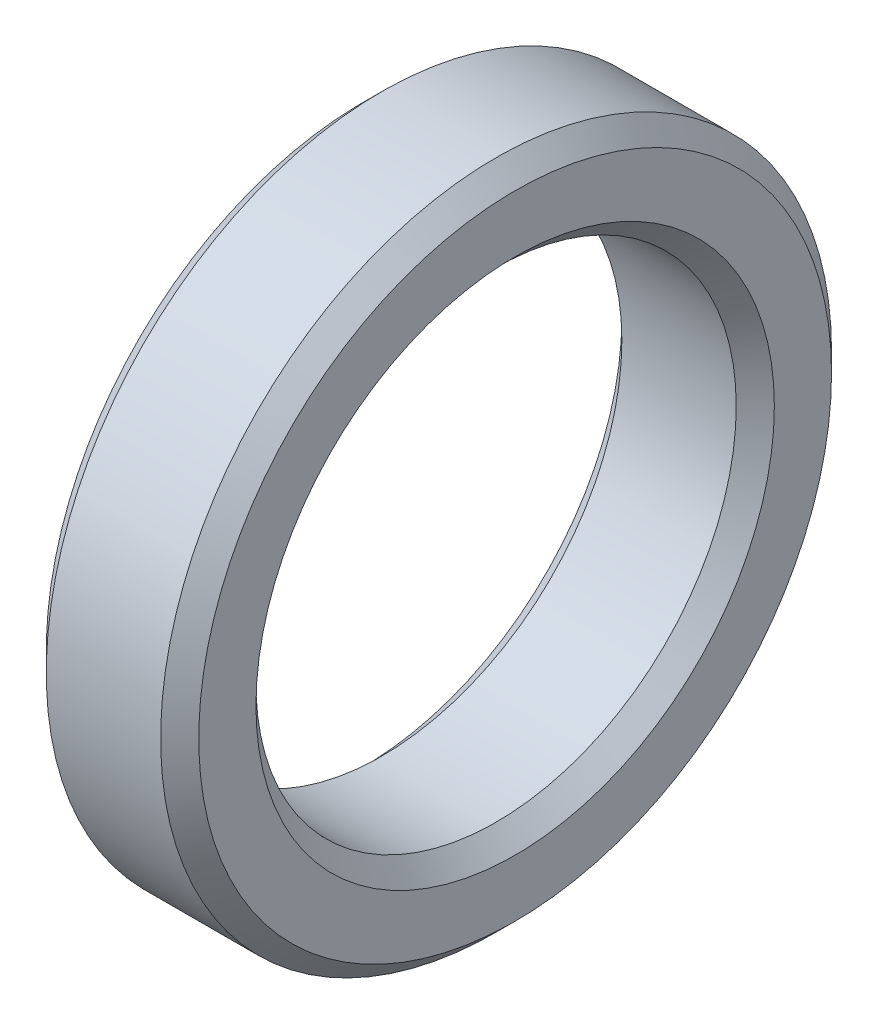
SolidWorks part; units mm, degrees
ref_plane "Спереди" through (0, 0, 0) normal (0, 0, 1) x (1, 0, 0)
ref_plane "Сверху" through (0, 0, 0) normal (0, 1, 0) x (1, 0, 0)
ref_plane "Справа" through (0, 0, 0) normal (1, 0, 0) x (0, 0, -1)
sketch "Sketch1" plane through (0, 0, 0) normal (1, 0, 0) x (0, 0, -1)
  circle A0 centre (0, 0) radius 8.8
  circle A1 centre (0, 0) radius 6.3
  dimension "D1" = 17.6
  dimension "D2" = 12.6
extrude "Boss-Extrude1" add sketch "Sketch1" along normal blind 4
chamfer "Chamfer1" distance 0.5 angle 45 2 edges at (0, 0, -8.8) (4, 0, -8.8)
chamfer "Chamfer2" distance 0.5 angle 45 2 edges at (0, 0, -6.3) (4, 0, -6.3)
